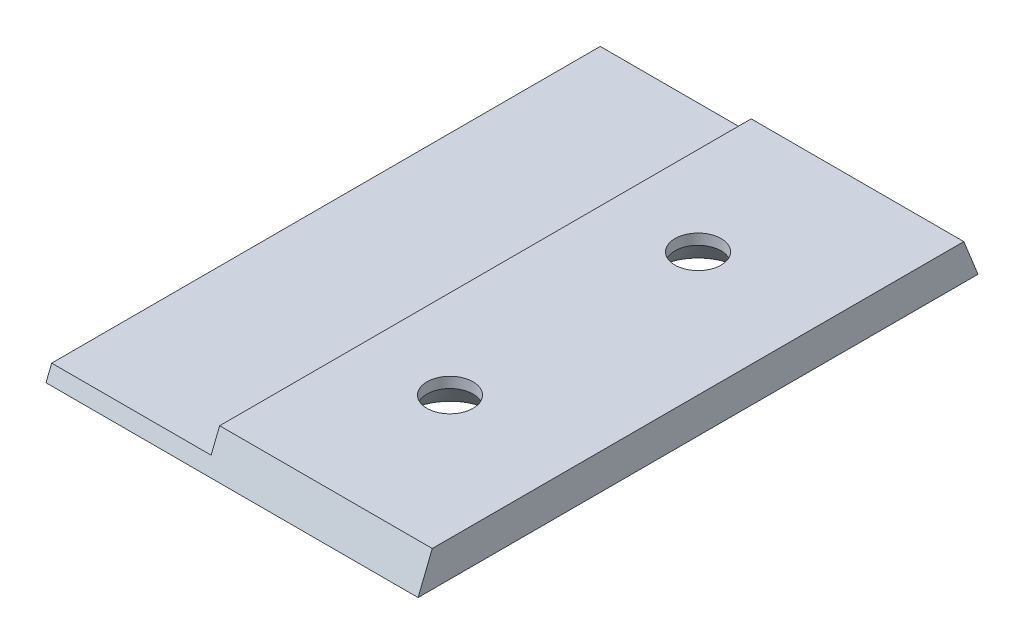
SolidWorks part; units mm, degrees
ref_plane "前视基准面" through (0, 0, 0) normal (0, 0, 1) x (1, 0, 0)
ref_plane "上视基准面" through (0, 0, 0) normal (0, 1, 0) x (1, 0, 0)
ref_plane "右视基准面" through (0, 0, 0) normal (1, 0, 0) x (0, 0, -1)
sketch "草图1" plane through (0, 0, 0) normal (0, 1, 0) x (1, 0, 0)
  line L1 (-52.5, -79) -> (52.5, -79)
  line L2 (-52.5, -79) -> (-52.5, 79)
  line L3 (-52.5, 79) -> (52.5, 79)
  line L4 (52.5, -79) -> (52.5, 79)
  line L5 (-52.5, -79) -> (52.5, 79) construction
  line L6 (-52.5, 79) -> (52.5, -79) construction
  point P0 (0, 0)
  dimension "D1" = 158
  dimension "D2" = 105
extrude "凸台-拉伸1" add sketch "草图1" along normal blind 10
sketch "草图2" plane through (0, 0, 0) normal (0, -1, 0) x (1, 0, 0)
  line L0 (52.5, 79) -> (52.5, -79) construction
  circle A0 centre (17.5, 35) radius 6.5
  dimension "D1" = 13
  dimension "D2" = 35
  dimension "D3" = 35
extrude "切除-拉伸1" cut sketch "草图2" against normal up to next
chamfer "倒角1" distance 5.5 distance2 7 1 edges at (17.5, 0, 28.5)
pattern_linear "阵列(线性)1" count 2 spacing 70 along (0, 0, -1) of "切除-拉伸1", "倒角1"
sketch "草图3" plane through (52.5, 0, 0) normal (1, 0, 0) x (0, 0, -1)
  line L0 (-79, 10) -> (-79, 0)
  line L1 (-79, 0) -> (-75.0003, 10)
  line L2 (-79, 10) -> (79, 10) construction
  line L3 (-75.0003, 10) -> (-79, 10)
  line L4 (79, 10) -> (79, 0)
  line L5 (79, 0) -> (75.0003, 10)
  line L6 (75.0003, 10) -> (79, 10)
  line L7 (-79, 0) -> (79, 0) construction
  dimension "D1" = 68.2
  dimension "D2" = 68.2
extrude "切除-拉伸2" cut sketch "草图3" against normal up to next
sketch "草图4" plane through (0, 10, 0) normal (0, 1, 0) x (1, 0, 0)
  line L0 (-52.5, 79) -> (-7.5, 79)
  line L1 (52.5, 79) -> (-52.5, 79) construction
  line L2 (-7.5, 79) -> (-7.5, -79)
  line L3 (-52.5, -79) -> (52.5, -79) construction
  line L4 (-7.5, -79) -> (-52.5, -79)
  line L5 (-52.5, -79) -> (-52.5, 79)
  dimension "D1" = 45
extrude "切除-拉伸3" cut sketch "草图4" against normal blind 6
